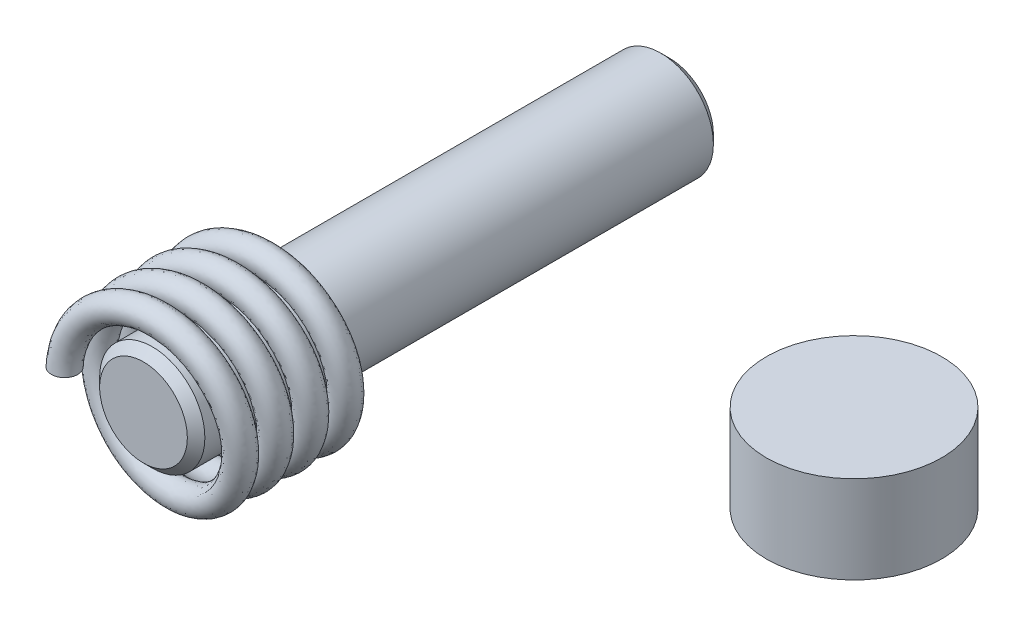
SolidWorks part; units mm, degrees
ref_plane "Front Plane" through (0, 0, 0) normal (0, 0, 1) x (1, 0, 0)
ref_plane "Top Plane" through (0, 0, 0) normal (0, 1, 0) x (1, 0, 0)
ref_plane "Right Plane" through (0, 0, 0) normal (1, 0, 0) x (0, 0, -1)
sketch "Sketch1" plane through (0, 0, 0) normal (0, 0, 1) x (1, 0, 0)
  circle A0 centre (0, 0) radius 0.6
  dimension "D1" = 1.2
extrude "Boss-Extrude1" add sketch "Sketch1" along normal mid plane 6
chamfer "Chamfer1" distance 0.1 angle 45 2 edges at (0.6, 0, -3) (0.6, 0, 3)
sketch "Sketch2" plane through (0, 0, 0) normal (0, 1, 0) x (1, 0, 0)
  circle A0 centre (5, 0.1041) radius 1
  dimension "D1" = 2
  dimension "D2" = 5
extrude "Boss-Extrude2" add sketch "Sketch2" along normal blind 1 separate body
sketch "Sketch5" plane through (0, 0, 3) normal (0, 0, 1) x (1, 0, 0)
  circle A0 centre (0, 0) radius 0.9
  dimension "D1" = 1.8
curve "Helix/Spiral2" pitch 0.4 height 1.5 turns 3.75
sketch "Sketch7" plane through (0, 0, 0) normal (1, 0, 0) x (0, 0, -1)
  circle A0 centre (-1.5, -0.9) radius 0.15
  dimension "D1" = 0.3
sweep "Sweep2" add profiles "Sketch7" path "Helix/Spiral2"
